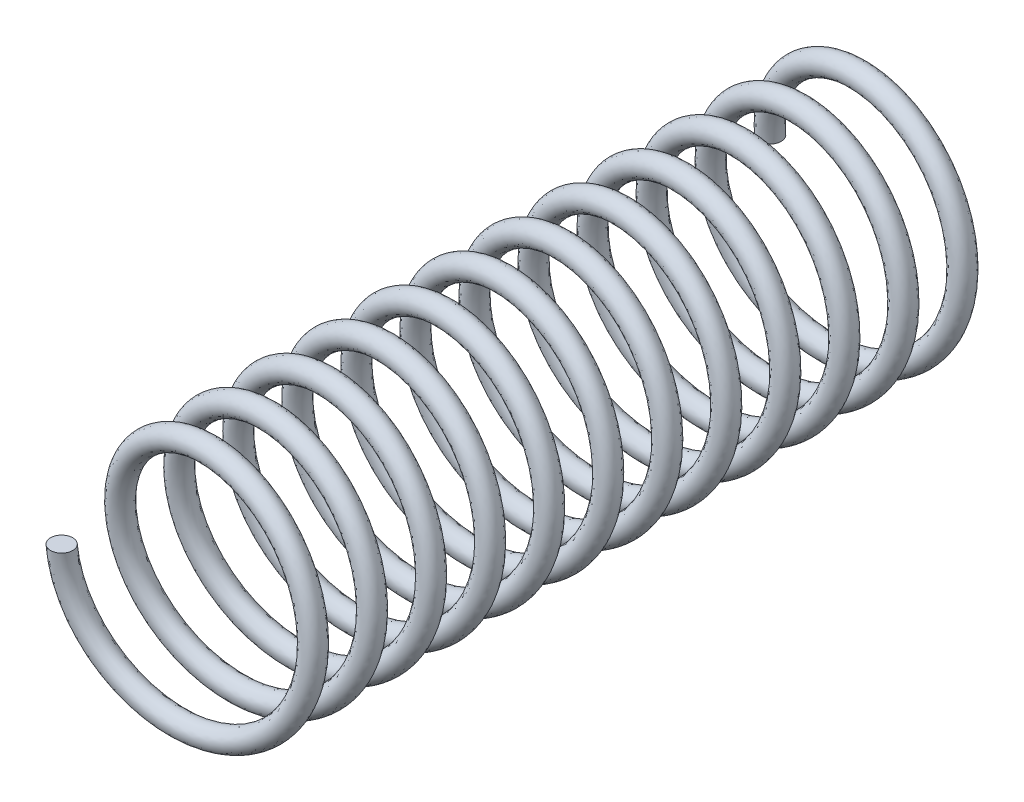
SolidWorks part; units mm, degrees
ref_plane "Front Plane" through (0, 0, 0) normal (0, 0, 1) x (1, 0, 0)
ref_plane "Top Plane" through (0, 0, 0) normal (0, 1, 0) x (1, 0, 0)
ref_plane "Right Plane" through (0, 0, 0) normal (1, 0, 0) x (0, 0, -1)
sketch "Sketch1" plane through (0, 0, 0) normal (0, 0, 1) x (1, 0, 0)
  circle A0 centre (0, 0) radius 7.5
  dimension "D1" = 15
curve "Helix/Spiral1" pitch 4 height 48 turns 12
sketch "Sketch2" plane through (0, 0, 0) normal (0, 1, 0) x (1, 0, 0)
  circle A0 centre (-7.5, 0) radius 0.75
  spline S0 degree 3 poles (-7.5, 0) (-7.5, -0.0828) (-7.1095, -0.2502) (-5.4414, -0.4999) (-2.9448, -0.75) (0, -1) (2.9448, -1.25) (5.4414, -1.5) (7.1095, -1.75) (7.6953, -2) (7.1095, -2.25) (5.4414, -2.5) (2.9448, -2.75) (0, -3) (-2.9448, -3.25) (-5.4414, -3.5) (-7.1095, -3.75) (-7.6953, -4) (-7.1095, -4.25) (-5.4414, -4.5) (-2.9448, -4.75) (0, -5) (2.9448, -5.25) (5.4414, -5.5) (7.1095, -5.75) (7.6953, -6) (7.1095, -6.25) (5.4414, -6.5) (2.9448, -6.75) (0, -7) (-2.9448, -7.25) (-5.4414, -7.5) (-7.1095, -7.75) (-7.6953, -8) (-7.1095, -8.25) (-5.4414, -8.5) (-2.9448, -8.75) (0, -9) (2.9448, -9.25) (5.4414, -9.5) (7.1095, -9.75) (7.6953, -10) (7.1095, -10.25) (5.4414, -10.5) (2.9448, -10.75) (0, -11) (-2.9448, -11.25) (-5.4414, -11.5) (-7.1095, -11.75) (-7.6953, -12) (-7.1095, -12.25) (-5.4414, -12.5) (-2.9448, -12.75) (0, -13) (2.9448, -13.25) (5.4414, -13.5) (7.1095, -13.75) (7.6953, -14) (7.1095, -14.25) (5.4414, -14.5) (2.9448, -14.75) (0, -15) (-2.9448, -15.25) (-5.4414, -15.5) (-7.1095, -15.75) (-7.6953, -16) (-7.1095, -16.25) (-5.4414, -16.5) (-2.9448, -16.75) (0, -17) (2.9448, -17.25) (5.4414, -17.5) (7.1095, -17.75) (7.6953, -18) (7.1095, -18.25) (5.4414, -18.5) (2.9448, -18.75) (0, -19) (-2.9448, -19.25) (-5.4414, -19.5) (-7.1095, -19.75) (-7.6953, -20) (-7.1095, -20.25) (-5.4414, -20.5) (-2.9448, -20.75) (0, -21) (2.9448, -21.25) (5.4414, -21.5) (7.1095, -21.75) (7.6953, -22) (7.1095, -22.25) (5.4414, -22.5) (2.9448, -22.75) (0, -23) (-2.9448, -23.25) (-5.4414, -23.5) (-7.1095, -23.75) (-7.6953, -24) (-7.1095, -24.25) (-5.4414, -24.5) (-2.9448, -24.75) (0, -25) (2.9448, -25.25) (5.4414, -25.5) (7.1095, -25.75) (7.6953, -26) (7.1095, -26.25) (5.4414, -26.5) (2.9448, -26.75) (0, -27) (-2.9448, -27.25) (-5.4414, -27.5) (-7.1095, -27.75) (-7.6953, -28) (-7.1095, -28.25) (-5.4414, -28.5) (-2.9448, -28.75) (0, -29) (2.9448, -29.25) (5.4414, -29.5) (7.1095, -29.75) (7.6953, -30) (7.1095, -30.25) (5.4414, -30.5) (2.9448, -30.75) (0, -31) (-2.9448, -31.25) (-5.4414, -31.5) (-7.1095, -31.75) (-7.6953, -32) (-7.1095, -32.25) (-5.4414, -32.5) (-2.9448, -32.75) (0, -33) (2.9448, -33.25) (5.4414, -33.5) (7.1095, -33.75) (7.6953, -34) (7.1095, -34.25) (5.4414, -34.5) (2.9448, -34.75) (0, -35) (-2.9448, -35.25) (-5.4414, -35.5) (-7.1095, -35.75) (-7.6953, -36) (-7.1095, -36.25) (-5.4414, -36.5) (-2.9448, -36.75) (0, -37) (2.9448, -37.25) (5.4414, -37.5) (7.1095, -37.75) (7.6953, -38) (7.1095, -38.25) (5.4414, -38.5) (2.9448, -38.75) (0, -39) (-2.9448, -39.25) (-5.4414, -39.5) (-7.1095, -39.75) (-7.6953, -40) (-7.1095, -40.25) (-5.4414, -40.5) (-2.9448, -40.75) (0, -41) (2.9448, -41.25) (5.4414, -41.5) (7.1095, -41.75) (7.6953, -42) (7.1095, -42.25) (5.4414, -42.5) (2.9448, -42.75) (0, -43) (-2.9448, -43.25) (-5.4414, -43.5) (-7.1095, -43.75) (-7.6953, -44) (-7.1095, -44.25) (-5.4414, -44.5) (-2.9448, -44.75) (0, -45) (2.9448, -45.25) (5.4414, -45.5) (7.1095, -45.75) (7.6953, -46) (7.1095, -46.25) (5.4414, -46.5) (2.9448, -46.75) (0, -47) (-2.9448, -47.25) (-5.4414, -47.5001) (-7.1095, -47.7498) (-7.5, -47.9172) (-7.5, -48) knots 0 0 0 0 0.005208 0.010417 0.015625 0.020833 0.026042 0.03125 0.036458 0.041667 0.046875 0.052083 0.057292 0.0625 0.067708 0.072917 0.078125 0.083333 0.088542 0.09375 0.098958 0.104167 0.109375 0.114583 0.119792 0.125 0.130208 0.135417 0.140625 0.145833 0.151042 0.15625 0.161458 0.166667 0.171875 0.177083 0.182292 0.1875 0.192708 0.197917 0.203125 0.208333 0.213542 0.21875 0.223958 0.229167 0.234375 0.239583 0.244792 0.25 0.255208 0.260417 0.265625 0.270833 0.276042 0.28125 0.286458 0.291667 0.296875 0.302083 0.307292 0.3125 0.317708 0.322917 0.328125 0.333333 0.338542 0.34375 0.348958 0.354167 0.359375 0.364583 0.369792 0.375 0.380208 0.385417 0.390625 0.395833 0.401042 0.40625 0.411458 0.416667 0.421875 0.427083 0.432292 0.4375 0.442708 0.447917 0.453125 0.458333 0.463542 0.46875 0.473958 0.479167 0.484375 0.489583 0.494792 0.5 0.505208 0.510417 0.515625 0.520833 0.526042 0.53125 0.536458 0.541667 0.546875 0.552083 0.557292 0.5625 0.567708 0.572917 0.578125 0.583333 0.588542 0.59375 0.598958 0.604167 0.609375 0.614583 0.619792 0.625 0.630208 0.635417 0.640625 0.645833 0.651042 0.65625 0.661458 0.666667 0.671875 0.677083 0.682292 0.6875 0.692708 0.697917 0.703125 0.708333 0.713542 0.71875 0.723958 0.729167 0.734375 0.739583 0.744792 0.75 0.755208 0.760417 0.765625 0.770833 0.776042 0.78125 0.786458 0.791667 0.796875 0.802083 0.807292 0.8125 0.817708 0.822917 0.828125 0.833333 0.838542 0.84375 0.848958 0.854167 0.859375 0.864583 0.869792 0.875 0.880208 0.885417 0.890625 0.895833 0.901042 0.90625 0.911458 0.916667 0.921875 0.927083 0.932292 0.9375 0.942708 0.947917 0.953125 0.958333 0.963542 0.96875 0.973958 0.979167 0.984375 0.989583 0.994792 1 1 1 1 construction
  point P4 (-7.5, 0)
  dimension "D1" = 1.5
sweep "Sweep1" add profiles "Sketch2" path "Helix/Spiral1"
